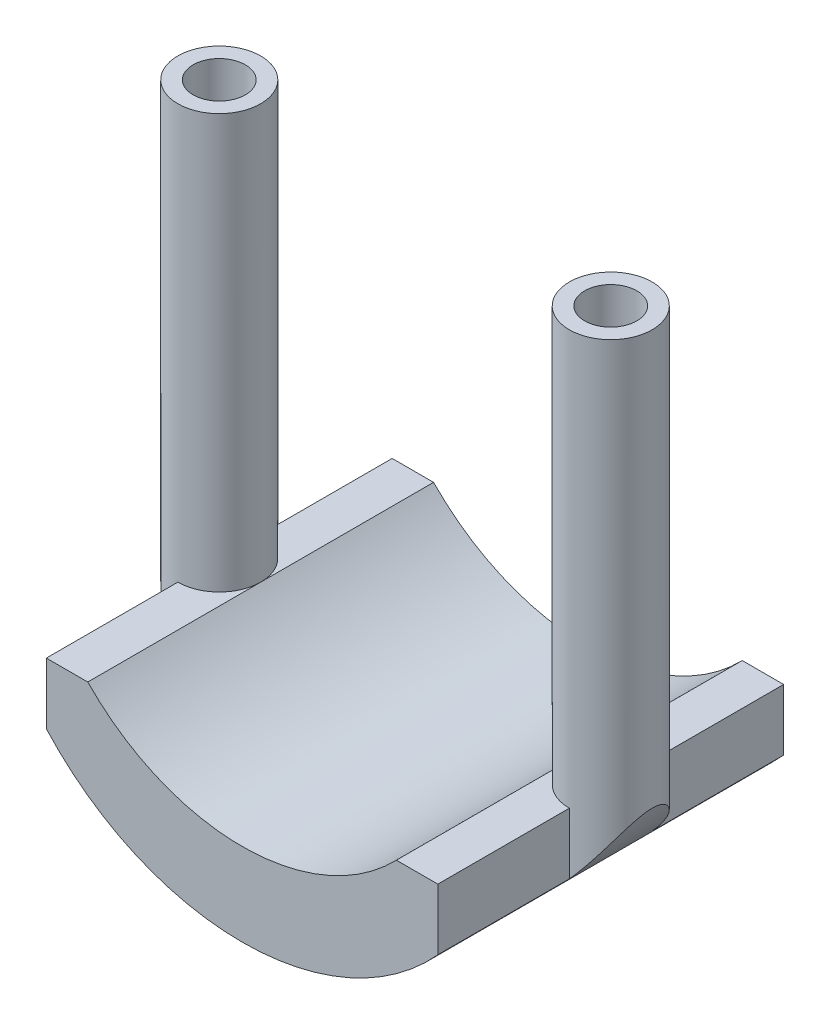
SolidWorks part; units mm, degrees
ref_plane "Front Plane" through (0, 0, 0) normal (0, 0, 1) x (1, 0, 0)
ref_plane "Top Plane" through (0, 0, 0) normal (0, 1, 0) x (1, 0, 0)
ref_plane "Right Plane" through (0, 0, 0) normal (1, 0, 0) x (0, 0, -1)
sketch "Sketch1" plane through (0, 0, 0) normal (0, 1, 0) x (1, 0, 0)
  line L0 (-15, 0) -> (15, 0) construction
  circle A0 centre (-15, 0) radius 3.175
  circle A1 centre (15, 0) radius 3.175
  point P4 (0, 0)
  dimension "D2" = 6.35
  dimension "D3" = 6.35
  dimension "D1" = 30
extrude "Boss-Extrude1" add sketch "Sketch1" along normal blind 31.75
sketch "Sketch2" plane through (0, 0, 0) normal (0, -1, 0) x (1, 0, 0)
  line L2 (-15, 3.175) -> (-15, 13.25)
  line L3 (-15, -3.175) -> (-15, -13.25)
  line L4 (15, 3.175) -> (15, 13.25)
  line L5 (15, 13.25) -> (-15, 13.25)
  line L6 (15, -3.175) -> (15, -13.25)
  line L7 (15, -13.25) -> (-15, -13.25)
  circle A0 centre (-15, 0) radius 3.175 construction
  circle A1 centre (15, 0) radius 3.175 construction
  arc A2 (-15, 3.175) -> (-15, -3.175) centre (-15, 0) ccw
  arc A3 (15, 3.175) -> (15, -3.175) centre (15, 0) cw
  dimension "D1" = 10.075
extrude "Boss-Extrude2" add sketch "Sketch2" along normal blind 20
sketch "Sketch4" plane through (0, 31.75, 0) normal (0, 1, 0) x (1, 0, 0)
  circle A0 centre (-15, 0) radius 2
  circle A1 centre (15, 0) radius 2
  dimension "D1" = 4
  dimension "D2" = 4
sketch "Sketch5" plane through (0, 0, 13.25) normal (0, 0, 1) x (1, 0, 0)
  line L0 (0, -20) -> (0, -5) construction
  line L1 (15, -20) -> (-15, -20) construction
  line L2 (-18.175, 0) -> (-18.175, -20)
  line L3 (-11.825, 0) -> (11.825, 0)
  line L4 (0, -5) -> (0, -11.35) construction
  line L5 (-18.175, -20) -> (18.175, -20)
  line L6 (-18.175, 31.75) -> (-18.175, -20) construction
  line L7 (18.175, -20) -> (18.175, 0)
  line L10 (18.175, -20) -> (18.175, 31.75) construction
  arc A0 (-11.825, 0) -> (11.825, 0) centre (0, 11.4831) ccw
  arc A1 (-18.175, 0) -> (18.175, 0) centre (0, 8.877) ccw
  point P8 (0, -5)
  point P15 (0, -11.35)
  point P18 (0, -11.35)
  line M3 (-15, 0) -> (-15, -20)
  line M4 (-15, -20) -> (15, -20)
  line M5 (15, -20) -> (15, 0)
  dimension "D1" = 15
  dimension "D2" = 6.35
extrude "Cut-Extrude2" cut sketch "Sketch5" against normal through all contours A1 M3 M4 M5 | A1 L2 L5 M3 | A1 L5 L7 M5 | A0 L3
extrude "Cut-Extrude3" cut sketch "Sketch4" against normal blind 3.175 contours A0 | A1
